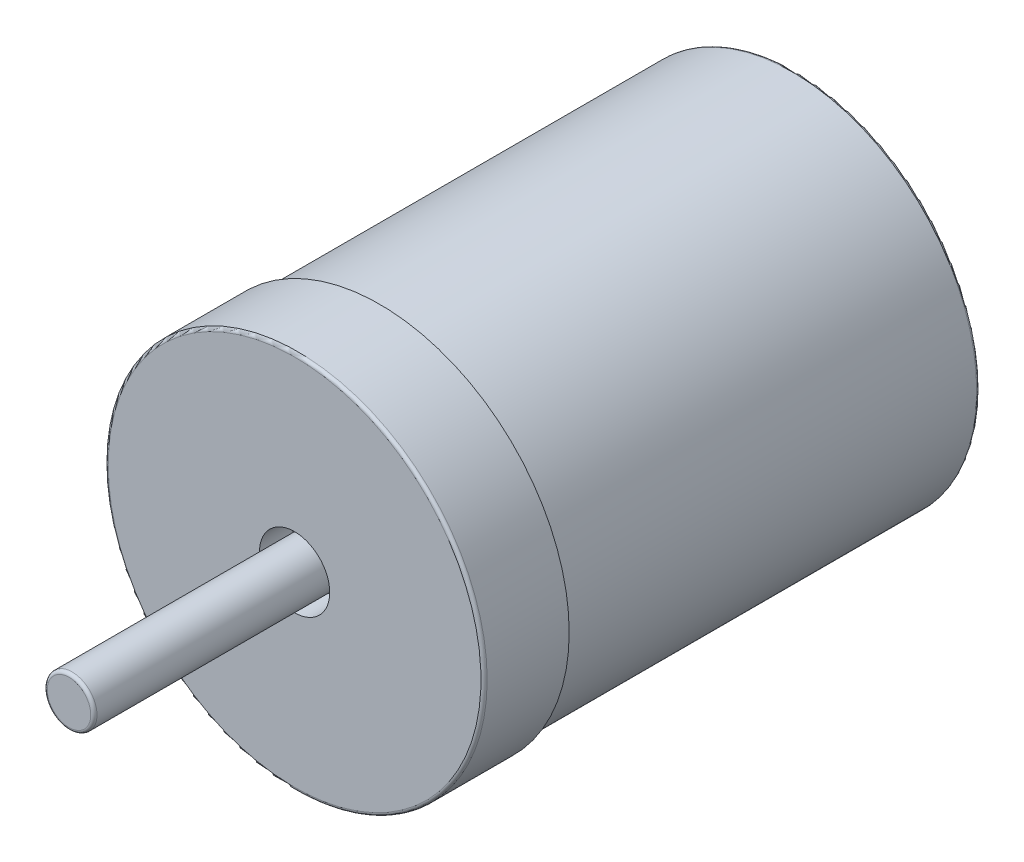
SolidWorks part; units mm, degrees
ref_plane "Front Plane" through (0, 0, 0) normal (0, 0, 1) x (1, 0, 0)
ref_plane "Top Plane" through (0, 0, 0) normal (0, 1, 0) x (1, 0, 0)
ref_plane "Right Plane" through (0, 0, 0) normal (1, 0, 0) x (0, 0, -1)
sketch "Sketch1" plane through (0, 0, 0) normal (1, 0, 0) x (0, 0, -1)
  line L0 (13.7, 30.5) -> (13.7, 29.5975)
  line L3 (0, 30.5) -> (13.7, 30.5)
  line L4 (80.7, 11.5852) -> (80.7, 29.5975)
  line L5 (-36.3086, 0) -> (90.3914, 0)
  line L6 (-36.3086, 0) -> (-36.3086, 4)
  line L7 (-36.3086, 4) -> (5.4138, 4)
  line L8 (90.3914, 0) -> (90.3914, 4)
  line L9 (0, 5.6529) -> (0, 30.5)
  line L11 (80.7, 11.5852) -> (88.1645, 11.5852)
  line L12 (88.1645, 4) -> (88.1645, 11.5852)
  line L13 (13.7, 29.5975) -> (80.7, 29.5975)
  line L14 (88.1645, 4) -> (90.3914, 4)
  line L17 (0, 5.6529) -> (5.4138, 5.6529)
  line L18 (5.4138, 4) -> (5.4138, 5.6529)
  point P20 (88.1645, 4)
  dimension "D3" = 126.7
  dimension "D4" = 67
  dimension "D5" = 4
revolve "Revolve1" add sketch "Sketch1" angle 360 about L5
fillet "Fillet2" radius 0.5 4 edges at (4, 0, -90.3914) (4, 0, 36.3086) (29.5975, 0, -80.7) (30.5, 0, 0)
